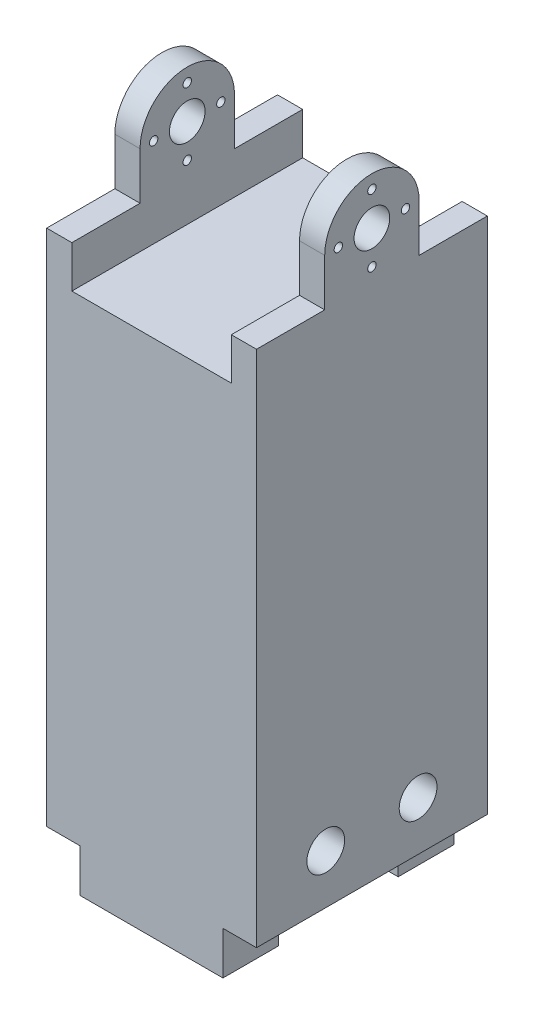
SolidWorks part; units mm, degrees
ref_plane "Front Plane" through (0, 0, 0) normal (0, 0, 1) x (1, 0, 0)
ref_plane "Top Plane" through (0, 0, 0) normal (0, 1, 0) x (1, 0, 0)
ref_plane "Right Plane" through (0, 0, 0) normal (1, 0, 0) x (0, 0, -1)
sketch "Sketch1" plane through (0, 0, 0) normal (0, 0, 1) x (1, 0, 0)
  line L1 (-25, 0) -> (25, 0)
  line L2 (-25, 0) -> (-25, -170)
  line L3 (-25, -170) -> (25, -170)
  line L4 (25, 0) -> (25, -170)
  dimension "D1" = 170
  dimension "D2" = 50
extrude "Boss-Extrude1" add sketch "Sketch1" against normal blind 55
sketch "Sketch2" plane through (0, 0, 0) normal (0, 0, 1) x (1, 0, 0)
  line L0 (25, 0) -> (-25, 0) construction
  line L1 (-17, 0) -> (17, 0)
  line L2 (-17, 0) -> (-17, -27)
  line L3 (-17, -27) -> (17, -27)
  line L4 (17, 0) -> (17, -27)
  line L5 (-25, 0) -> (-25, -170) construction
  dimension "D1" = 8
  dimension "D2" = 34
  dimension "D3" = 27
extrude "Cut-Extrude1" cut sketch "Sketch2" against normal through all
sketch "Sketch3" plane through (25, 0, 0) normal (1, 0, 0) x (0, 0, -1)
  line L0 (0, -170) -> (0, 0) construction
  line L1 (55, -27) -> (0, -27)
  line L2 (55, -27) -> (55, -24)
  line L3 (55, -24) -> (0, -24)
  line L4 (0, -27) -> (0, -24)
  line L5 (55, -170) -> (55, 0) construction
  line L7 (0, 0) -> (10, 0)
  line L8 (0, 0) -> (0, -24)
  line L9 (0, -24) -> (10, -24)
  line L10 (10, 0) -> (10, -24)
  line L11 (55, 0) -> (45, 0)
  line L12 (55, 0) -> (55, -24)
  line L13 (55, -24) -> (45, -24)
  line L14 (45, 0) -> (45, -24)
  circle A0 centre (27.5, -12.75) radius 10.25
  circle A1 centre (27.5, -12.75) radius 4.25
  circle A2 centre (27.5, -12.75) radius 8
  circle A3 centre (27.5, -4.75) radius 1
  circle A4 centre (35.5, -12.75) radius 1
  circle A5 centre (27.5, -20.75) radius 1
  circle A6 centre (19.5, -12.75) radius 1
  point P32 (27.5, -12.75)
  line M7 (0, 0) -> (0, -170)
  line M9 (55, -170) -> (55, 0)
  line M10 (55, 0) -> (0, 0)
  dimension "D2" = 11.25
  dimension "D3" = 27.5
  dimension "D4" = 20.5
  dimension "D7" = 8.5
  dimension "D8" = 16
  dimension "D9" = 4
  dimension "D1" = 3
  dimension "D5" = 10
  dimension "D6" = 10
extrude "Cut-Extrude2" cut sketch "Sketch3" against normal through all contours L14 L3 M10 M9 | L10 L3 M10 M7 | A2 A6 | A2 A6 | A1 | A2 A5 | A2 A5 | A2 A4 | A2 A4 | A2 A3 | A2 A3
sketch "Sketch4" plane through (0, 0, -10) normal (0, 0, 1) x (1, 0, 0)
  line L0 (-25, -24) -> (-17, -24) construction
  line L1 (-17, 0) -> (-19, 0)
  line L2 (-17, 0) -> (-17, -24)
  line L3 (-17, -24) -> (-19, -24)
  line L4 (-19, 0) -> (-19, -24)
  line L5 (0, 0) -> (0, -13.53) construction
  line L6 (19, 0) -> (19, -24)
  line L7 (17, -24) -> (19, -24)
  line L8 (17, 0) -> (17, -24)
  line L9 (17, 0) -> (19, 0)
  dimension "D1" = 2
extrude "Cut-Extrude3" cut sketch "Sketch4" against normal through all
sketch "Sketch5" plane through (25, 0, 0) normal (1, 0, 0) x (0, 0, -1)
  line L1 (10, 0) -> (45, 0)
  line L2 (10, 0) -> (10, -24)
  line L3 (10, -24) -> (45, -24)
  line L4 (45, 0) -> (45, -24)
  line L5 (38.75, -12.75) -> (38.75, -24)
  line L6 (16.25, -12.75) -> (10, -12.75)
  line L7 (16.25, -12.75) -> (16.25, -24)
  line L8 (16.25, -24) -> (10, -24)
  line L9 (10, -12.75) -> (10, -24)
  line L10 (38.75, -12.75) -> (45, -12.75)
  line L11 (38.75, -12.75) -> (38.75, -24)
  line L12 (38.75, -24) -> (45, -24)
  line L13 (45, -12.75) -> (45, -24)
  circle A0 centre (27.5, -12.75) radius 11.25
  line M8 (45, -24) -> (45, 0)
  line M9 (45, 0) -> (10, 0)
  line M10 (10, 0) -> (10, -24)
  dimension "D1" = 22.5
extrude "Cut-Extrude4" cut sketch "Sketch5" against normal through all contours A0 L10 L4 L6 M9 M10 | L7 L6 L2 L3 | L10 L5 L3 M8
sketch "Sketch6" plane through (0, 0, 0) normal (0, 0, 1) x (1, 0, 0)
  line L1 (-19, -24) -> (19, -24)
  line L2 (-19, -24) -> (-19, -34)
  line L3 (-19, -34) -> (19, -34)
  line L4 (19, -24) -> (19, -34)
  dimension "D1" = 10
extrude "Cut-Extrude5" cut sketch "Sketch6" against normal through all
sketch "Sketch8" plane through (25, 0, 0) normal (1, 0, 0) x (0, 0, -1)
  line L0 (55, -170) -> (55, -24) construction
  line L1 (0, -170) -> (0, -24) construction
  line L2 (41.75, -132.5) -> (13.25, -132.5)
  line L3 (27.5, -132.5) -> (27.5, -179)
  line L4 (41.75, -179) -> (13.25, -179)
  line L5 (13.25, -132.5) -> (13.25, -179)
  line L7 (41.75, -132.5) -> (41.75, -179)
  line L11 (27.5, -167.75) -> (55, -167.75)
  line L12 (27.5, -167.75) -> (27.5, -170)
  line L13 (27.5, -170) -> (55, -170)
  line L14 (55, -167.75) -> (55, -170)
  line L16 (27.5, -167.75) -> (0, -167.75)
  line L17 (27.5, -167.75) -> (27.5, -170)
  line L18 (27.5, -170) -> (0, -170)
  line L19 (0, -167.75) -> (0, -170)
  circle A0 centre (27.5, -167.75) radius 10.25
  circle A1 centre (27.5, -12.75) radius 10.25
  line M4 (0, -24) -> (0, -170)
  line M5 (0, -170) -> (55, -170)
  line M6 (55, -170) -> (55, -24)
  dimension "D1" = 27.5
  dimension "D2" = 20.5
  dimension "D3" = 155
  dimension "D4" = 14.25
  dimension "D5" = 11.25
  dimension "D6" = 46.5
  dimension "D7" = 13.25
extrude "Cut-Extrude7" cut sketch "Sketch8" against normal through all contours A0 L3 L2 L5 L16 | A0 L11 L7 L2 L3 | L11 L7 M5 M6 | L5 L16 M4 M5 | A0 L16 L5 M5 | A0 L13 L7 L11 | L3 A0 L16 | L11 A0 L3 | L16 A0 L18 L3 | A0 L11 L3 M5
sketch "Sketch9" plane through (0, 0, 0) normal (0, 0, 1) x (1, 0, 0)
  line L0 (-25, -167.75) -> (25, -167.75) construction
  line L1 (17, -167.75) -> (-17, -167.75)
  line L2 (17, -167.75) -> (17, -132.5)
  line L3 (17, -132.5) -> (-17, -132.5)
  line L4 (-17, -167.75) -> (-17, -132.5)
  line L5 (-25, -132.5) -> (25, -132.5) construction
  line L7 (-25, -24) -> (-25, -167.75) construction
  line L9 (25, -167.75) -> (25, -24) construction
  dimension "D1" = 8
  dimension "D2" = 8
extrude "Cut-Extrude8" cut sketch "Sketch9" against normal through all
sketch "Sketch11" plane through (25, 0, 0) normal (1, 0, 0) x (0, 0, -1)
  line L0 (27.5, -157.5) -> (27.5, -147.5)
  line L2 (27.5, -147.5) -> (55, -147.5)
  line L3 (27.5, -147.5) -> (27.5, -167.75)
  line L4 (27.5, -167.75) -> (55, -167.75)
  line L5 (55, -147.5) -> (55, -167.75)
  line L6 (27.5, -147.5) -> (0, -147.5)
  line L7 (27.5, -147.5) -> (27.5, -167.75)
  line L8 (27.5, -167.75) -> (0, -167.75)
  line L9 (0, -147.5) -> (0, -167.75)
  circle A0 centre (27.5, -167.75) radius 10.25
  arc A1 (38.75, -12.75) -> (16.25, -12.75) centre (27.5, -12.75) ccw construction
  line M1 (0, -167.75) -> (13.25, -167.75)
  line M2 (13.25, -167.75) -> (13.25, -132.5)
  line M4 (41.75, -132.5) -> (41.75, -167.75)
  line M5 (41.75, -167.75) -> (55, -167.75)
  line M6 (55, -167.75) -> (55, -24)
  line M12 (0, -24) -> (0, -167.75)
  dimension "D1" = 155
  dimension "D2" = 20.5
  dimension "D3" = 10
extrude "Cut-Extrude9" cut sketch "Sketch11" against normal through all contours A0 L0 L6 L8 M2 | A0 L4 L2 L0 M4 | L2 M4 M5 M6 | L6 M2 M12 M1
sketch "Sketch12" plane through (25, 0, 0) normal (1, 0, 0) x (0, 0, -1)
  line L1 (13.25, -132.5) -> (41.75, -132.5)
  line L2 (13.25, -132.5) -> (13.25, -147.5)
  line L3 (13.25, -147.5) -> (41.75, -147.5)
  line L4 (41.75, -132.5) -> (41.75, -147.5)
extrude "Boss-Extrude2" add sketch "Sketch12" against normal blind 8
ref_plane "Plane1" through (0, 0, 0) normal (1, 0, 0) x (0, 0, -1)
mirror "Mirror1" about plane through (0, 0, 0) normal (1, 0, 0) of "Boss-Extrude2"
sketch "Sketch14" plane through (0, 0, 0) normal (0, 0, 1) x (1, 0, 0)
  line L0 (17, -148.55) -> (17, -158.75) construction
  line L1 (-17, -132.5) -> (17, -132.5)
  line L2 (-17, -132.5) -> (-17, -147.5)
  line L3 (-17, -147.5) -> (17, -147.5)
  line L4 (17, -132.5) -> (17, -147.5)
  line L5 (-17, -147.5) -> (17, -147.5)
  line L6 (-17, -147.5) -> (-17, -157.75)
  line L7 (-17, -157.75) -> (17, -157.75)
  line L8 (17, -147.5) -> (17, -157.75)
  line M11 (-17, -147.5) -> (-17, -132.5)
  line M12 (-17, -132.5) -> (17, -132.5)
  line M13 (17, -132.5) -> (17, -147.5)
  dimension "D1" = 10.25
extrude "Boss-Extrude3" add sketch "Sketch14" against normal blind 13.25 contours L3 M11 M13 M12 | L8 L3 L6 L7
ref_plane "Plane2" through (0, 0, -27.5) normal (0, 0, 1) x (1, 0, 0)
mirror "Mirror2" about plane through (0, 0, -27.5) normal (0, 0, 1) of "Boss-Extrude3"
sketch "Sketch16" plane through (25, 0, 0) normal (1, 0, 0) x (0, 0, -1)
  line L0 (41.75, -132.5) -> (13.25, -132.5) construction
  line L1 (13.25, -132.5) -> (13.25, -147.5) construction
  circle A1 centre (16.5, -135.75) radius 2.5
  circle A2 centre (16.5, -135.75) radius 4.5
  circle A3 centre (38.5, -135.75) radius 4.5
  dimension "D1" = 3.25
  dimension "D2" = 3.25
  dimension "D3" = 2
extrude "Cut-Extrude13" cut sketch "Sketch16" against normal blind 8 contours A1 | A2 A1 | A3
mirror "Mirror3" about plane through (0, 0, 0) normal (1, 0, 0) of "Cut-Extrude13"
